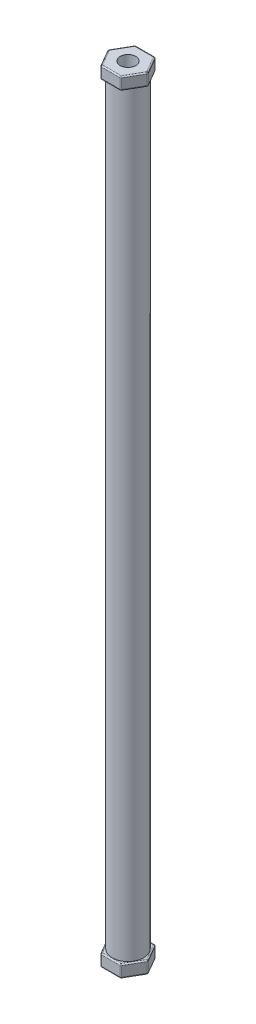
SolidWorks part; units mm, degrees
ref_plane "Front Plane" through (0, 0, 0) normal (0, 0, 1) x (1, 0, 0)
ref_plane "Top Plane" through (0, 0, 0) normal (0, 1, 0) x (1, 0, 0)
ref_plane "Right Plane" through (0, 0, 0) normal (1, 0, 0) x (0, 0, -1)
sketch "Sketch1" plane through (0, 0, 0) normal (0, 1, 0) x (1, 0, 0)
  circle A0 centre (0, 0) radius 6.35
  circle A1 centre (0, 0) radius 3.175
  dimension "D1" = 12.7
extrude "Boss-Extrude1" add sketch "Sketch1" along normal blind 304.8
ref_plane "Plane1" through (0, 152.4, 0) normal (0, 1, 0) x (1, 0, 0)
sketch "Sketch2" plane through (0, 304.8, 0) normal (0, 1, 0) x (1, 0, 0)
  line L1 (-8.0656, 0) -> (-4.0328, -6.985)
  line L2 (-4.0328, -6.985) -> (4.0328, -6.985)
  line L3 (4.0328, -6.985) -> (8.0656, 0)
  line L4 (8.0656, 0) -> (4.0328, 6.985)
  line L5 (4.0328, 6.985) -> (-4.0328, 6.985)
  line L6 (-4.0328, 6.985) -> (-8.0656, 0)
  circle A0 centre (0, 0) radius 6.985 construction
  circle A1 centre (0, 0) radius 3.175
  dimension "D1" = 13.97
extrude "Boss-Extrude2" add sketch "Sketch2" along normal blind 5
fillet "Fillet1" radius 0.5 18 edges at (6.0492, 304.8, -3.4925) (4.0328, 307.3, -6.985) (8.0656, 307.3, 0) (-4.0328, 307.3, -6.985) (-6.0492, 304.8, -3.4925) (-8.0656, 307.3, 0) (-6.0492, 304.8, 3.4925) (-4.0328, 307.3, 6.985) (0, 304.8, 6.985) (6.0492, 304.8, 3.4925) (4.0328, 307.3, 6.985) (6.0492, 309.8, 3.4925) (6.0492, 309.8, -3.4925) (0, 309.8, -6.985) (-6.0492, 309.8, -3.4925) (-6.0492, 309.8, 3.4925) (0, 309.8, 6.985) (0, 304.8, -6.985)
mirror "Mirror1" about plane through (0, 152.4, 0) normal (0, 1, 0) of "Fillet1", "Boss-Extrude2"
